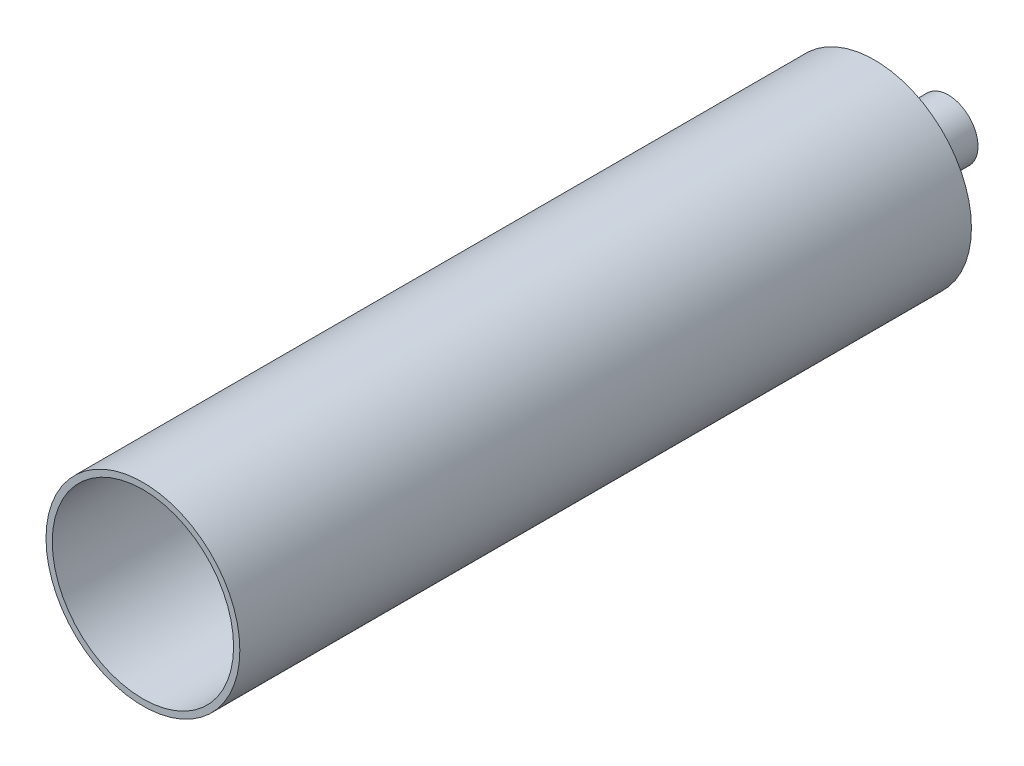
SolidWorks part; units mm, degrees
ref_plane "Front Plane" through (0, 0, 0) normal (0, 0, 1) x (1, 0, 0)
ref_plane "Top Plane" through (0, 0, 0) normal (0, 1, 0) x (1, 0, 0)
ref_plane "Right Plane" through (0, 0, 0) normal (1, 0, 0) x (0, 0, -1)
sketch "Sketch1" plane through (0, 0, 0) normal (0, 0, 1) x (1, 0, 0)
  circle A0 centre (0, 0) radius 15.5
  circle A1 centre (0, 0) radius 14.5
  dimension "D1" = 31
  dimension "D2" = 1
extrude "Boss-Extrude1" add sketch "Sketch1" along normal blind 117
sketch "Sketch4" plane through (0, 0, 0) normal (1, 0, 0) x (0, 0, -1)
  line L0 (0, -14.5) -> (0, 14.5) construction
  line L1 (0, 0) -> (9.0167, 0) construction
  line L2 (4.3, -4.75) -> (0, -15.5)
  line L5 (0, 15.5) -> (0, -15.5)
  line L10 (4.3, 0) -> (3.3, 0)
  line L11 (3.3, 0) -> (3.3, -4.75)
  line L12 (3.3, -4.75) -> (0, -13)
  line L13 (0, -13) -> (0, -15.5)
  line L15 (0, -15.5) -> (0, 15.5) construction
  line L16 (4.3, -4.75) -> (11.8, -4.75)
  line L17 (11.8, -4.75) -> (11.8, 0)
  line L18 (11.8, 0) -> (4.3, 0)
  point P0 (4.3, 0)
  dimension "D1" = 4.3
  dimension "D2" = 1
  dimension "D3" = 7.5
  dimension "D4" = 4.75
revolve "Revolve1" add sketch "Sketch4" angle 360 about L1
